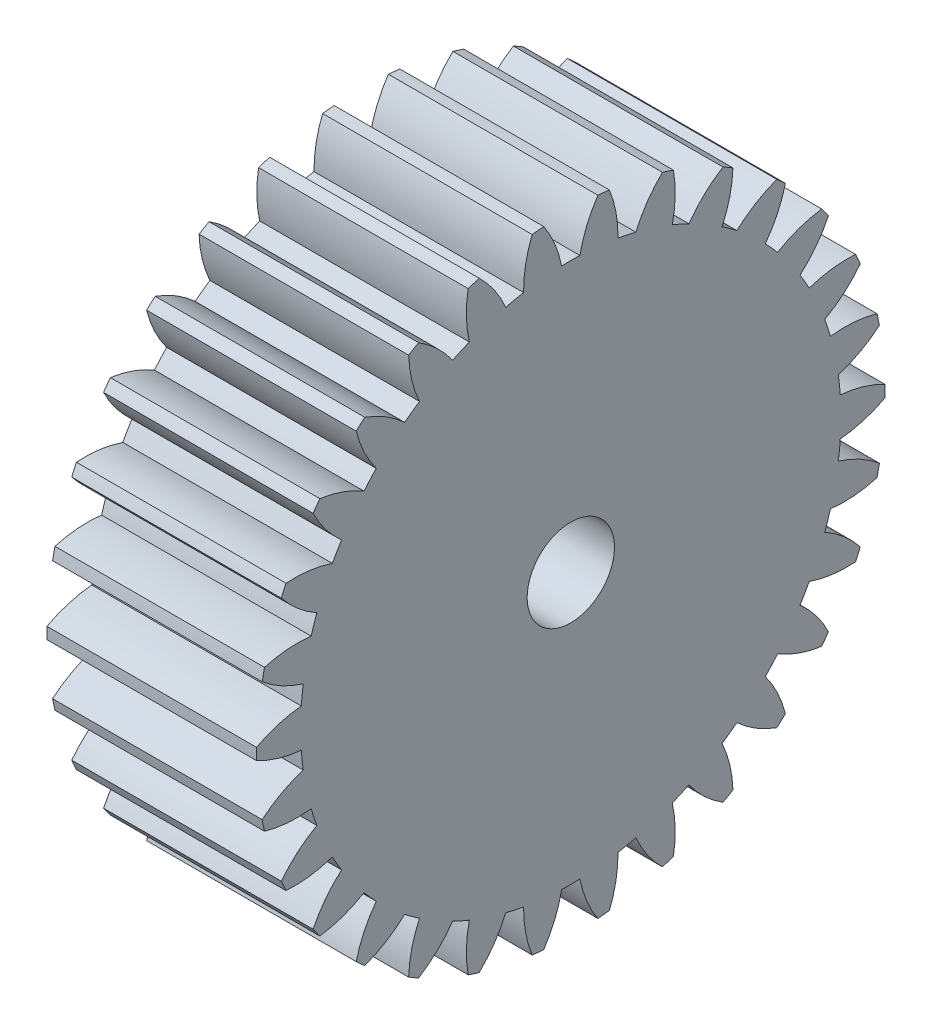
SolidWorks part; units mm, degrees
ref_plane "Plane1" through (0, 0, 0) normal (0, 0, 1) x (1, 0, 0)
ref_plane "Plane2" through (0, 0, 0) normal (0, 1, 0) x (1, 0, 0)
ref_plane "Plane3" through (0, 0, 0) normal (1, 0, 0) x (0, 0, -1)
other "Configuration Table"
sketch "HoldingSke" plane through (0, 0, 0) normal (0, 1, 0) x (1, 0, 0)
  line L0 (0, 0) -> (0.7698, -0.4444)
  line L1 (-15, 0) -> (100, 0) construction
  line L2 (0, 0) -> (-2.1039, 2.3779)
  line L3 (0, 0) -> (-11.863, 4.5341)
  line L4 (0, 0) -> (7.479, 4.318)
  line L5 (0, 0) -> (-46.8476, -17.4728)
  line L6 (0, 0) -> (-9.9476, -6.7116)
  line L7 (-2.1039, 2.3779) -> (8.6586, 51.2059)
  line L8 (-76.2, 54.61) -> (-75.3, 54.61)
  line L9 (-71.009, 38.7566) -> (-53.1078, 45.2721)
  line L10 (-76.2, 71.12) -> (104.1128, 71.12)
  line L11 (0, 0) -> (-12, 0)
  line L12 (-76.2, 101.6) -> (-76.158, 101.6)
  line L13 (24.9733, 27.94) -> (52.9518, 28.4284)
  line L14 (24.9733, 27.94) -> (24.9743, 27.94)
  line L15 (24.9733, 27.94) -> (100.4006, 29.5858)
  line L16 (-63.627, -1.125) -> (-12.827, -1.125)
  circle A0 centre (0, 0) radius 2.5
  circle A1 centre (0, 0) radius 15.4677
  circle A2 centre (0, 0) radius 37.5
  circle A3 centre (0, 0) radius 2.5
  dimension "MHD" = 30.9355
  dimension "Hub_dia" = 75
  dimension "Num_teeth" = 30
  dimension "Pitch" = 0.8889
  dimension "Overall_len" = 50
  dimension "Show_teeth" = 30
  dimension "Thickness" = 12
  dimension "OAL" = 50.0001
  dimension "Ap" = 20
  dimension "H" = 19.05
  dimension "Pitch_radius" = 180.3128
  dimension "Width" = 12
  dimension "Backlash" = 0.042
  dimension "Addendum_fac" = 1
  dimension "Dedendum_fac" = 1.25
  dimension "Clearance_fac" = 0.25
  dimension "Dedendum_add" = 0.001
  dimension "Module" = 1.125
sketch "BasProSke" plane through (0, 0, 0) normal (0, 1, 0) x (1, 0, 0)
  line L0 (-10, 0) -> (60, 0) construction
  line L1 (0, 0) -> (0, 18)
  line L2 (0, 0) -> (12, 0)
  line L3 (12, 0) -> (12, 18)
  line L4 (12, 18) -> (0, 18)
  dimension "Thickness" = 12
  dimension "Diameter" = 36
revolve "Base-Revolve" add sketch "BasProSke" angle 360 about L0
sketch "TooCutSke" plane through (0, 0, 0) normal (1, 0, 0) x (0, 0, -1)
  line L1 (0, 0) -> (0, 107) construction
  line L2 (0, 0) -> (-0.9567, 16.8479) construction
  line L3 (0, 0) -> (-3.5238, 33.5265) construction
  line L4 (-0.9567, 16.8479) -> (-1.7619, 16.7632) construction
  arc A0 (0.5235, 15.4589) -> (-0.5235, 15.4589) centre (0, 0) ccw
  arc A1 (1.5687, 17.957) -> (-1.5687, 17.957) centre (0, 0) ccw
  circle A2 centre (0, 0) radius 16.875 construction
  circle A3 centre (0, 0) radius 15.8573 construction
  arc A4 (-0.5235, 15.4589) -> (-1.5687, 17.957) centre (-7.1465, 14.1556) ccw
  arc A5 (1.5687, 17.957) -> (0.5235, 15.4589) centre (7.1465, 14.1556) ccw
  dimension "Root_dia" = 30.9355
  dimension "Overcut_dia" = 36.0508
  dimension "Pitch_dia" = 33.75
  dimension "Base_dia" = 31.7146
  dimension "Flank_rad" = 6.75
  dimension "Half_ang" = 6
  dimension "Half_CT" = 0.8097
extrude "ToothCut" cut sketch "TooCutSke" along normal through all
fillet "Breaks" [suppressed] radius 0.0225
fillet "RootFillets" [suppressed] radius 0.2822
pattern_circular "TeethCuts" count 30 every 12 about axis through (-10, 0, 0) along (1, 0, 0) of "ToothCut", "RootFillets", "Breaks"
sketch "HubNeaOneSke" plane through (0, 0, 0) normal (-1, 0, 0) x (0, 0, 1)
  circle A0 centre (0, 0) radius 15.4677
  dimension "Diameter" = 30.9355
extrude "HubNearOne" [suppressed] add sketch "HubNeaOneSke" along normal blind 38.0001
sketch "HubNeaBotSke" plane through (0, 0, 0) normal (-1, 0, 0) x (0, 0, 1)
  circle A0 centre (0, 0) radius 15.4677
  dimension "Diameter" = 30.9355
extrude "HubNearBoth" [suppressed] add sketch "HubNeaBotSke" along normal blind 19
ref_plane "FarPln" through (12, 0, 0) normal (1, 0, 0) x (0, 0, -1)
sketch "HubFarSke" plane through (12, 0, 0) normal (1, 0, 0) x (0, 0, -1)
  circle A0 centre (0, 0) radius 15.4677
  dimension "Diameter" = 30.9355
extrude "HubFar" [suppressed] add sketch "HubFarSke" along normal blind 19
sketch "BorSke" plane through (0, 0, 0) normal (1, 0, 0) x (0, 0, -1)
  circle A0 centre (0, 0) radius 2.5
extrude "Bore" cut sketch "BorSke" along normal mid plane 100.0001
sketch "KeySke" plane through (0, 0, 0) normal (1, 0, 0) x (0, 0, -1)
  line L0 (-1, 0) -> (-1, 3.4)
  line L1 (-1, 3.4) -> (1, 3.4)
  line L2 (1, 3.4) -> (1, 0)
  line L3 (0, 0) -> (0, 34) construction
  line L4 (-1, 0) -> (1, 0)
  dimension "Width" = 2
extrude "Keyway" [suppressed] cut sketch "KeySke" along normal mid plane 100.0001
pattern_circular "Keyway2" [suppressed] count 2 every 90 about axis through (-10, 0, 0) along (1, 0, 0)
equation "' \"Module@HoldingSke\" = 6.35"
equation "' \"Num_teeth@HoldingSke\" = 12"
equation "' \"Ap@HoldingSke\" =  20"
equation "' \"Ap@HoldingSke\" = 20"
equation "' \"Width@HoldingSke\" = 0.5 * 25.4"
equation "' \"Hub_dia@HoldingSke\"= 1 * 25.4"
equation "' \"Hub_dia@HoldingSke\" = 1 * 25.4"
equation "' \"Overall_len@HoldingSke\" = 1.0 * 25.4"
equation "' \"Bore@HoldingSke\" = 0.75 * 25.4"
equation "' \"T_dim@HoldingSke\" = 0.1 * 25.4"
equation "' \"Width@KeySke\" = 0.25 * 25.4"
equation "' \"Show_teeth@HoldingSke\" = 13"
equation "' \"Backlash@HoldingSke\" = 0.009 * 25.4"
equation "' \"Addendum_fac@HoldingSke\" = 1.0"
equation "' \"Dedendum_fac@HoldingSke\" = 1.25"
equation "' \"Dedendum_add@HoldingSke\" = 0.00005 * 25.4"
equation "' \"Clearance_fac@HoldingSke\" = 0.25"
equation "\"Pitch@HoldingSke\" = 1 / \"Module@HoldingSke\""
equation "\"Overcut_dia@TooCutSke\" = (\"Num_teeth@HoldingSke\" + 2 * \"Addendum_fac@HoldingSke\") / \"Pitch@HoldingSke\" + 0.002 * 25.4"
equation "\"Pitch_dia@TooCutSke\" = \"Num_teeth@HoldingSke\" / \"Pitch@HoldingSke\""
equation "\"Base_dia@TooCutSke\" = \"Num_teeth@HoldingSke\" / \"Pitch@HoldingSke\" * cos((\"Ap@HoldingSke\"  * 3.14159265 / 180))"
equation "\"Root_dia@TooCutSke\" = (\"Num_teeth@HoldingSke\" + 2) / \"Pitch@HoldingSke\" - 2 * (\"Addendum_fac@HoldingSke\" + \"Dedendum_fac@HoldingSke\") / \"Pitch@HoldingSke\" - \"Dedendum_add@HoldingSke\" * 2"
equation "\"Half_ang@TooCutSke\" = 180 / \"Num_teeth@HoldingSke\""
equation "\"Half_CT@TooCutSke\" = \"Num_teeth@HoldingSke\" / \"Pitch@HoldingSke\" * sin((3.14159265 / 2 / \"Num_teeth@HoldingSke\")) / 2 - 7 * \"Backlash@HoldingSke\" / 4"
equation "\"Flank_rad@TooCutSke\" = \"Num_teeth@HoldingSke\" / \"Pitch@HoldingSke\" / 5"
equation "\"Radius@RootFillets\" = \"Clearance_fac@HoldingSke\" / \"Pitch@HoldingSke\" + \"Dedendum_add@HoldingSke\""
equation "\"Break_rad@Breaks\" = 0.02 / \"Pitch@HoldingSke\""
equation "\"Thickness@HoldingSke\" = \"Width@HoldingSke\""
equation "\"OAL@HoldingSke\" = \"Thickness@HoldingSke\""
equation "\"MHD@HoldingSke\" = (\"Num_teeth@HoldingSke\" + 2) / \"Pitch@HoldingSke\" - 2 * (\"Addendum_fac@HoldingSke\" + \"Dedendum_fac@HoldingSke\")  / \"Pitch@HoldingSke\" - \"Dedendum_add@HoldingSke\" * 2"
equation "\"MBD@HoldingSke\" = (\"Num_teeth@HoldingSke\" + 2) / \"Pitch@HoldingSke\" - 2 * (\"Addendum_fac@HoldingSke\" + \"Dedendum_fac@HoldingSke\")  / \"Pitch@HoldingSke\" - \"Dedendum_add@HoldingSke\" * 2 - 0.002 * 25.4"
equation "\"MHD@HoldingSke\" = ((sgn( \"MHD@HoldingSke\" - \"Hub_dia@HoldingSke\" )-1)*( \"MHD@HoldingSke\" - \"Hub_dia@HoldingSke\" ))/-2+ \"Hub_dia@HoldingSke\""
equation "\"MBD@HoldingSke\" = ((sgn( \"MBD@HoldingSke\" - \"Bore@HoldingSke\" )-1)*( \"MBD@HoldingSke\" - \"Bore@HoldingSke\" ))/-2+ \"Bore@HoldingSke\""
equation "\"OAL@HoldingSke\" = ((sgn( \"OAL@HoldingSke\" - \"Overall_len@HoldingSke\" )+1)*( \"OAL@HoldingSke\" - \"Overall_len@HoldingSke\" ))/2 + \"Overall_len@HoldingSke\" + 0.000002 * 25.4"
equation "\"Num_teeth@TeethCuts\" = int( \"Show_teeth@HoldingSke\" ) + 1"
equation "\"Num_teeth@TeethCuts\" = ((sgn( \"Num_teeth@TeethCuts\" - \"Num_teeth@HoldingSke\" )-1)*( \"Num_teeth@TeethCuts\" - \"Num_teeth@HoldingSke\" ))/-2+ \"Num_teeth@HoldingSke\""
equation "\"Num_teeth@TeethCuts\" = ((sgn( \"Num_teeth@TeethCuts\" - 2.0)+1)*( \"Num_teeth@TeethCuts\" - 2.0))/2 +2.0"
equation "\"Angle@TeethCuts\" = 360.0 / \"Num_teeth@HoldingSke\""
equation "\"Diameter@BasProSke\" = (\"Num_teeth@HoldingSke\" + 2 * \"Addendum_fac@HoldingSke\") / \"Pitch@HoldingSke\""
equation "\"Thickness@BasProSke\"  = \"Thickness@HoldingSke\""
equation "' \"Fillet_rad@BasProSke\" =  \"Thickness@HoldingSke\" * 0.05"
equation "' \"Fillet_rad@BasProSke\" = \"Thickness@HoldingSke\" * 0.05"
equation "\"MHD@HoldingSke\" = ((sgn( \"MHD@HoldingSke\" - \"Root_dia@TooCutSke\" )-1)*( \"MHD@HoldingSke\" - \"Root_dia@TooCutSke\" ))/-2+ \"Root_dia@TooCutSke\""
equation "\"Diameter@HubNeaOneSke\" = \"MHD@HoldingSke\""
equation "\"Length@HubNearOne\" = \"OAL@HoldingSke\" - \"Thickness@BasProSke\""
equation "\"Diameter@HubNeaBotSke\" = \"MHD@HoldingSke\""
equation "\"Length@HubNearBoth\" = ( \"OAL@HoldingSke\" - \"Thickness@BasProSke\" ) / 2.0"
equation "\"Thickness@FarPln\" = \"Thickness@BasProSke\""
equation "\"Diameter@HubFarSke\" = \"MHD@HoldingSke\""
equation "\"Length@HubFar\" = ( \"OAL@HoldingSke\" - \"Thickness@BasProSke\" ) / 2.0"
equation "\"Diameter@BorSke\" = \"MBD@HoldingSke\""
equation "\"D1@Bore\" = \"OAL@HoldingSke\" * 2.0"
equation "\"D1@Keyway\" = \"OAL@HoldingSke\" * 2.0"
equation "\"Offset@KeySke\" = \"T_dim@HoldingSke\" + \"MBD@HoldingSke\" / 2.0"
